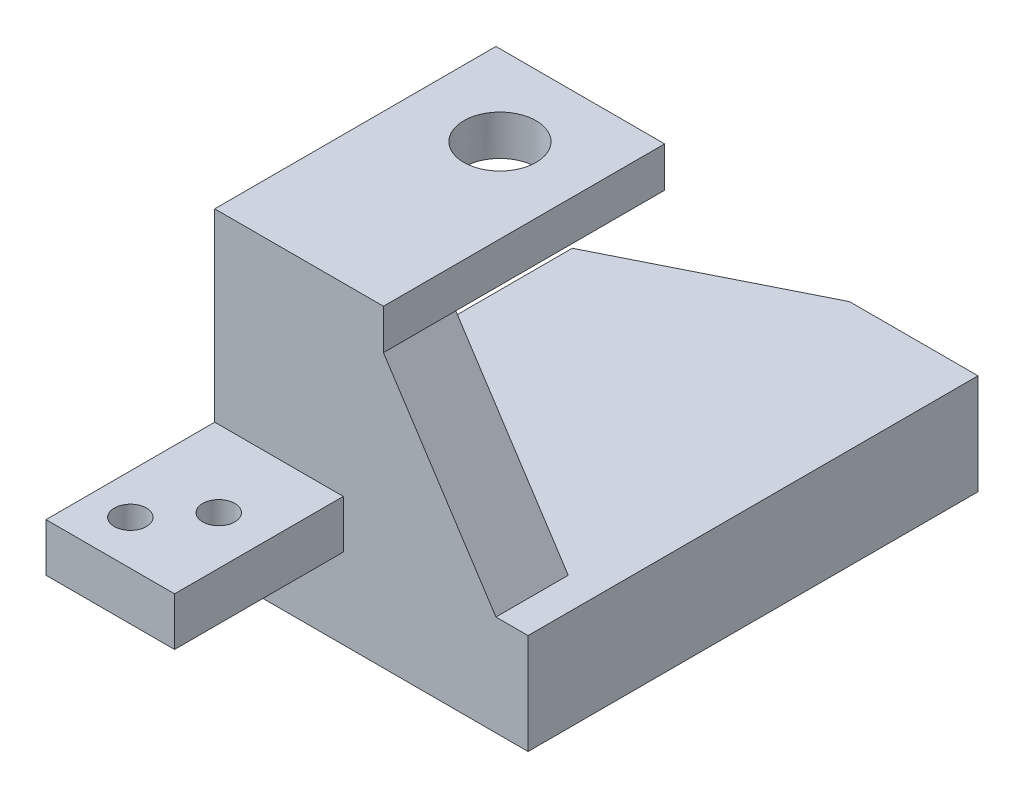
SolidWorks part; units mm, degrees
ref_plane "Front Plane" through (0, 0, 0) normal (0, 0, 1) x (1, 0, 0)
ref_plane "Top Plane" through (0, 0, 0) normal (0, 1, 0) x (1, 0, 0)
ref_plane "Right Plane" through (0, 0, 0) normal (1, 0, 0) x (0, 0, -1)
sketch "Sketch1" plane through (0, 0, 0) normal (0, 1, 0) x (1, 0, 0)
  line L0 (57.3076, 0) -> (135.3076, 0)
  line L1 (135.3076, 0) -> (135.3076, 112)
  line L4 (135.3076, 112) -> (103.3076, 112)
  line L6 (57.3076, 0) -> (57.3076, 89)
  line L7 (57.3076, 89) -> (103.3076, 112)
  dimension "D1" = 112
  dimension "D2" = 78
  dimension "D3" = 32
  dimension "D4" = 23
extrude "Boss-Extrude1" add sketch "Sketch1" against normal blind 25
sketch "Sketch2" plane through (0, 0, 0) normal (0, 0, 1) x (1, 0, 0)
  line L0 (127.3076, 0) -> (99.3076, 43)
  line L1 (57.3076, 0) -> (135.3076, 0) construction
  line L2 (99.3076, 43) -> (99.3076, 53)
  line L3 (127.3076, 0) -> (57.3076, 0)
  line L4 (57.3076, 0) -> (57.3076, 53)
  line L5 (57.3076, 53) -> (99.3076, 53)
  line L6 (57.3076, 53) -> (57.3076, -25)
  line M7 (135.3076, 0) -> (57.3076, 0)
  dimension "D1" = 8
  dimension "D2" = 78
  dimension "D3" = 10
  dimension "D4" = 42
extrude "Boss-Extrude2" add sketch "Sketch2" against normal blind 18 contours L5 L4 L0 L2 M7
sketch "Sketch3" plane through (0, 0, 0) normal (0, 0, 1) x (1, 0, 0)
  line L0 (57.3076, 53) -> (99.3076, 53)
  line L1 (99.3076, 53) -> (99.3076, 43)
  line L2 (99.3076, 43) -> (57.3076, 43)
  line L3 (57.3076, -25) -> (57.3076, 53) construction
  line L4 (57.3076, 43) -> (57.3076, 53)
extrude "Boss-Extrude3" add sketch "Sketch3" against normal blind 70
sketch "Sketch4" plane through (0, 53, 0) normal (0, 1, 0) x (1, 0, 0)
  line L0 (99.3076, 70) -> (57.3076, 70) construction
  line L1 (57.3076, 70) -> (57.3076, 0) construction
  circle A0 centre (78.3076, 50) radius 9
  dimension "D1" = 20
  dimension "D2" = 21
extrude "Cut-Extrude1" cut sketch "Sketch4" against normal up to next
sketch "Sketch5" plane through (57.3076, 0, 0) normal (-1, 0, 0) x (0, 0, 1)
  line L0 (0, -25) -> (0, 53) construction
  line L1 (0, -5) -> (42, -5)
  line L2 (0, -5) -> (0, 7)
  line L3 (0, 7) -> (42, 7)
  line L4 (42, -5) -> (42, 7)
  dimension "D1" = 20
  dimension "D2" = 42
  dimension "D3" = 12
extrude "Boss-Extrude4" add sketch "Sketch5" against normal blind 32
sketch "Sketch6" plane through (0, 7, 0) normal (0, 1, 0) x (1, 0, 0)
  line L0 (57.3076, -42) -> (57.3076, 0) construction
  line L1 (89.3076, -42) -> (57.3076, -42) construction
  circle A0 centre (67.3076, -31) radius 4
  circle A1 centre (77.3076, -19) radius 4
  dimension "D1" = 10
  dimension "D2" = 20
  dimension "D3" = 23
  dimension "D4" = 11
extrude "Cut-Extrude2" cut sketch "Sketch6" against normal up to next
